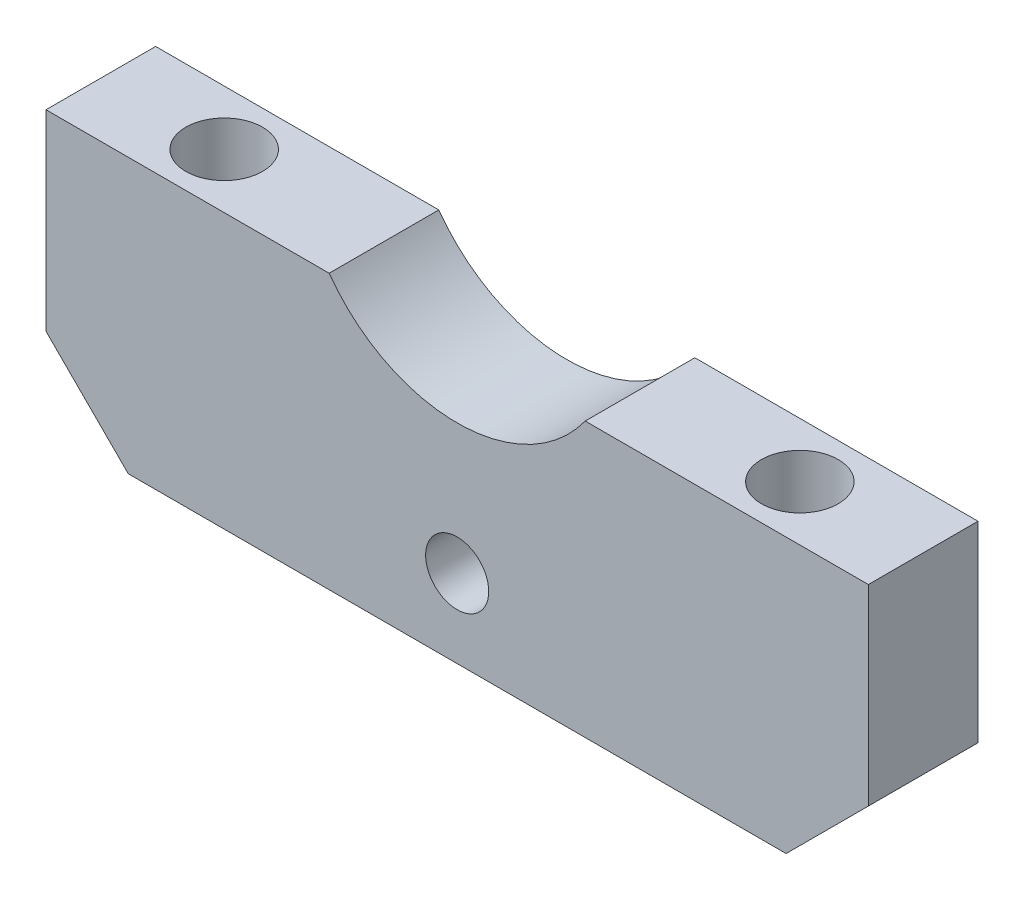
SolidWorks part; units mm, degrees
material "尼龙 101"
ref_plane "前视基准面" through (0, 0, 0) normal (0, 0, 1) x (1, 0, 0)
ref_plane "上视基准面" through (0, 0, 0) normal (0, 1, 0) x (1, 0, 0)
ref_plane "右视基准面" through (0, 0, 0) normal (1, 0, 0) x (0, 0, -1)
sketch "草图1" plane through (0, 0, 0) normal (0, 0, 1) x (1, 0, 0)
  line L1 (-15, -6.5) -> (15, -6.5)
  line L2 (-15, -6.5) -> (-15, 6.5)
  line L3 (-15, 6.5) -> (15, 6.5)
  line L4 (15, -6.5) -> (15, 6.5)
  line L5 (-15, -6.5) -> (15, 6.5) construction
  line L6 (-15, 6.5) -> (15, -6.5) construction
  point P0 (0, 0)
  dimension "D1" = 13
  dimension "D2" = 30
extrude "凸台-拉伸1" add sketch "草图1" along normal blind 4
sketch "草图3" plane through (0, 0, 4) normal (0, 0, 1) x (1, 0, 0)
  circle A0 centre (0, 9.8541) radius 5.75
  dimension "D1" = 11.5
extrude "切除-拉伸2" cut sketch "草图3" against normal blind 10
sketch "草图5" plane through (0, 0, 4) normal (0, 0, 1) x (1, 0, 0)
  line L0 (0, 9.8541) -> (0, -0.6459) construction
  circle A0 centre (0, 9.8541) radius 10.5 construction
  circle A1 centre (0, -0.6459) radius 1.15
  point P5 (0, -0.6459)
  dimension "D1" = 21
  dimension "D2" = 2.3
sketch "草图7" plane through (0, 0, 4) normal (0, 0, 1) x (1, 0, 0)
  line L1 (-15, -6.5) -> (15, -6.5)
  line L2 (-15, -6.5) -> (-15, -3.5)
  line L3 (-15, -3.5) -> (15, -3.5)
  line L4 (15, -6.5) -> (15, -3.5)
  line L5 (15, -6.5) -> (15, 6.5) construction
  dimension "D1" = 3
  dimension "D2" = 30
extrude "切除-拉伸3" cut sketch "草图7" against normal blind 10
sketch "草图8" plane through (0, -3.5, 0) normal (0, -1, 0) x (1, 0, 0)
  line L0 (-15, 0) -> (-15, 4) construction
  circle A0 centre (-10.5, 2) radius 1.4
  point P0 (-10.5, 2)
  dimension "D2" = 2.8
  dimension "D1" = 4.5
chamfer "倒角1" distance 3 angle 45 2 edges at (15, -3.5, 2) (-15, -3.5, 2)
extrude "切除-拉伸4" cut sketch "草图8" against normal through all
mirror "镜向1" about plane through (0, 0, 0) normal (1, 0, 0) of "切除-拉伸4"
extrude "切除-拉伸5" cut sketch "草图5" against normal blind 10 contours A1
